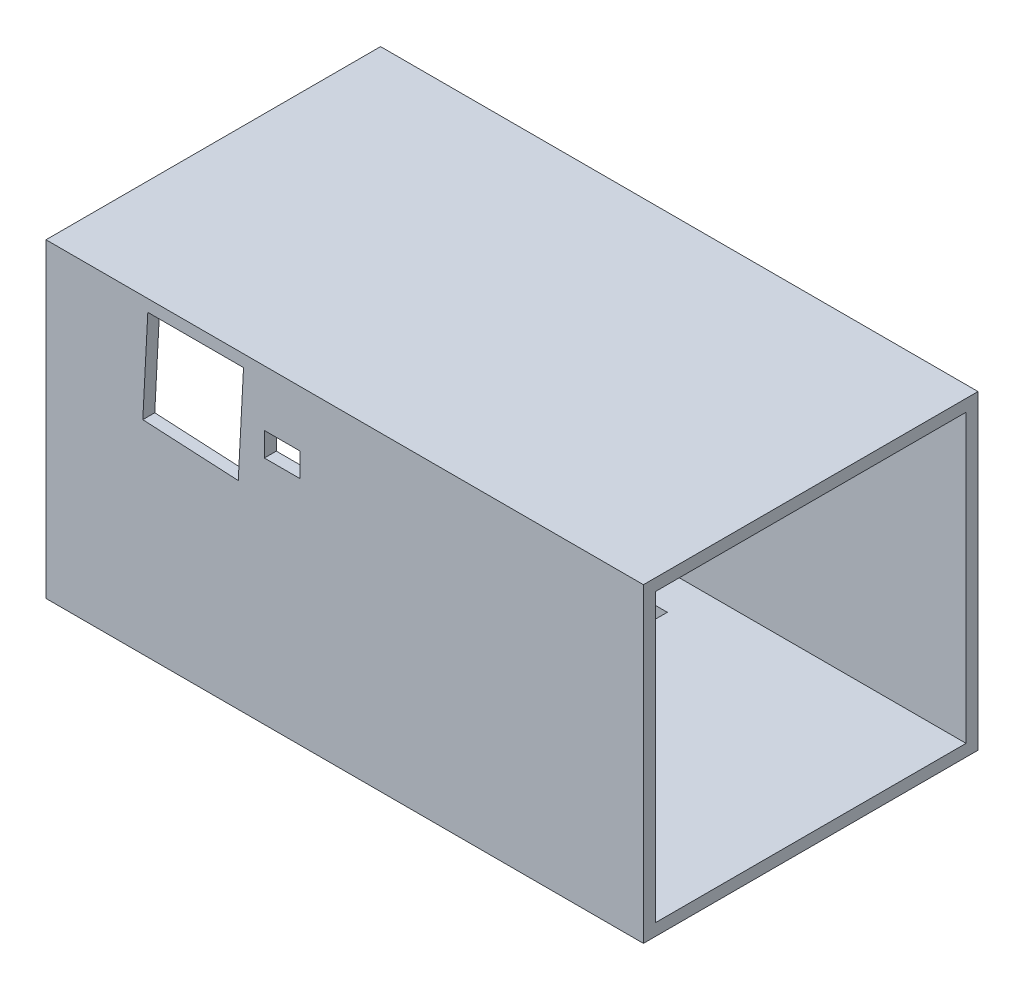
SolidWorks part; units mm, degrees
ref_plane "Front Plane" through (0, 0, 0) normal (0, 0, 1) x (1, 0, 0)
ref_plane "Top Plane" through (0, 0, 0) normal (0, 1, 0) x (1, 0, 0)
ref_plane "Right Plane" through (0, 0, 0) normal (1, 0, 0) x (0, 0, -1)
sketch "C" plane through (0, 0, 0) normal (0, 1, 0) x (1, 0, 0)
  line L1 (0, 0) -> (250, 0)
  line L2 (0, 0) -> (0, 70)
  line L3 (0, 70) -> (250, 70)
  line L4 (250, 0) -> (250, 70)
extrude "Boss-Extrude1" add sketch "C" along normal blind 5 contours L3 L4 L1 L2
sketch "Sketch2" plane through (0, 5, 0) normal (0, 1, 0) x (1, 0, 0)
  line L0 (250, 0) -> (250, 70) construction
  line L1 (0, 70) -> (250, 70)
  line L2 (0, 70) -> (0, 65)
  line L3 (0, 65) -> (250, 65)
  line L4 (250, 70) -> (250, 65)
extrude "Boss-Extrude2" add sketch "Sketch2" along normal blind 120
sketch "Sketch3" plane through (0, 0, -65) normal (0, 0, 1) x (1, 0, 0)
  line L0 (106.3733, 96.5861) -> (91.3733, 96.5861)
  line L5 (106.3733, 96.5861) -> (106.3733, 106.5861)
  line L10 (106.3733, 106.5861) -> (91.3733, 106.5861)
  line L11 (91.3733, 96.5861) -> (91.3733, 106.5861)
  line L17 (40.5093, 85.0548) -> (80.4545, 82.9614)
  line L18 (80.4545, 82.9614) -> (82.6576, 125)
  line L19 (250, 125) -> (0, 125) construction
  line L20 (80.4545, 82.9614) -> (82.6576, 125) construction
  line L21 (82.6576, 125) -> (42.6027, 125)
  line L22 (42.6027, 125) -> (40.5093, 85.0548) construction
  line L23 (40.5093, 85.0548) -> (42.6027, 125)
extrude "Cut-Extrude1" cut sketch "Sketch3" against normal blind 120
sketch "Sketch4" plane through (0, 0, 0) normal (0, -1, 0) x (1, 0, 0)
  line L1 (0, 0) -> (140, 0)
  line L2 (0, 0) -> (0, -50)
  line L3 (0, -50) -> (140, -50)
  line L4 (140, 0) -> (140, -50)
extrude "Cut-Extrude2" cut sketch "Sketch4" against normal blind 5
ref_plane "Plane1" through (0, 130, 0) normal (0, 1, 0) x (1, 0, 0)
sketch "Sketch5" plane through (0, 130, 0) normal (0, 1, 0) x (1, 0, 0)
  line L0 (0, 70) -> (0, 65) construction
  line L1 (0, 70) -> (250, 70)
  line L2 (0, 70) -> (0, 0)
  line L3 (0, 0) -> (250, 0)
  line L4 (250, 70) -> (250, 0)
extrude "Boss-Extrude3" add sketch "Sketch5" against normal blind 5
sketch "Sketch6" plane through (0, 130, 0) normal (0, 1, 0) x (1, 0, 0)
  line L1 (0, 0) -> (35, 0)
  line L2 (0, 0) -> (0, 31)
  line L3 (0, 31) -> (35, 31)
  line L4 (35, 0) -> (35, 31)
sketch "Sketch10" plane through (0, 0, -65) normal (0, 0, 1) x (1, 0, 0)
  line L0 (42.1106, 124.2205) -> (72.0695, 122.6505)
  line L1 (250, 125) -> (0, 125)
  line L2 (250, 125) -> (250, 5)
  line L3 (250, 5) -> (0, 5)
  line L4 (0, 125) -> (0, 5)
  line L5 (72.0695, 122.6505) -> (70.4994, 92.6916)
  line L6 (70.4994, 92.6916) -> (40.5405, 94.2617)
  line L7 (40.5405, 94.2617) -> (42.1106, 124.2205)
mirror "Mirror3" about plane through (0, 0, 0) normal (0, 0, 1) of bodies 109 117
sketch "Sketch19" plane through (0, 0, -65) normal (0, 0, 1) x (1, 0, 0)
  line L0 (250, 5) -> (250, 125)
  line L1 (250, 125) -> (0, 125)
  line L2 (0, 125) -> (0, 5)
  line L3 (0, 5) -> (250, 5)
  line L4 (147.1279, 102.6949) -> (147.913, 117.6743)
  line L5 (147.1279, 102.6949) -> (147.913, 117.6743) construction
  line L6 (147.913, 117.6743) -> (162.9614, 116.8856)
  line L7 (162.9614, 116.8856) -> (162.1074, 101.9098)
  line L8 (162.8924, 116.8893) -> (162.1074, 101.9098) construction
  line L9 (162.1074, 101.9098) -> (147.1279, 102.6949)
  line L10 (72.0695, 122.6505) -> (70.4994, 92.6916)
  line L11 (70.4994, 92.6916) -> (40.5405, 94.2617)
  line L12 (40.5405, 94.2617) -> (42.1106, 124.2205)
  line L13 (42.1106, 124.2205) -> (72.0695, 122.6505)
